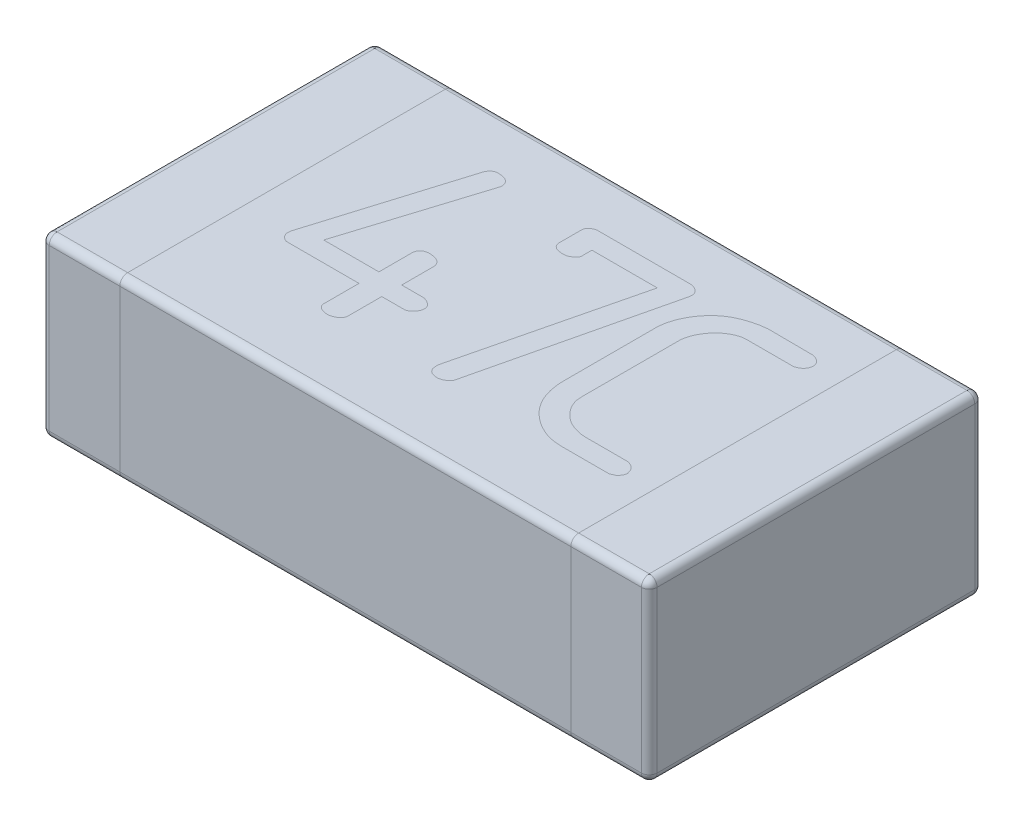
SolidWorks part; units mm, degrees
ref_plane "Front Plane" through (0, 0, 0) normal (0, 0, 1) x (1, 0, 0)
ref_plane "Top Plane" through (0, 0, 0) normal (0, 1, 0) x (1, 0, 0)
ref_plane "Right Plane" through (0, 0, 0) normal (1, 0, 0) x (0, 0, -1)
sketch "Sketch1" plane through (0, 0, 0) normal (0, 1, 0) x (1, 0, 0)
  line L1 (-0.755, -0.425) -> (0.755, -0.425)
  line L2 (-0.775, -0.405) -> (-0.775, 0.405)
  line L3 (-0.755, 0.425) -> (0.755, 0.425)
  line L4 (0.775, -0.405) -> (0.775, 0.405)
  line L5 (-0.775, -0.425) -> (0.775, 0.425) construction
  line L6 (-0.775, 0.425) -> (0.775, -0.425) construction
  arc A4 (-0.775, -0.405) -> (-0.755, -0.425) centre (-0.755, -0.405) ccw
  arc A5 (0.755, -0.425) -> (0.775, -0.405) centre (0.755, -0.405) ccw
  arc A6 (0.775, 0.405) -> (0.755, 0.425) centre (0.755, 0.405) ccw
  arc A7 (-0.755, 0.425) -> (-0.775, 0.405) centre (-0.755, 0.405) ccw
  point P0 (0, 0)
  dimension "D4" = 0.02
  dimension "D1" = 1.55
  dimension "D2" = 0.85
extrude "Boss-Extrude1" add sketch "Sketch1" along normal mid plane 0.45
sketch "Sketch3" plane through (0, 0.225, 0) normal (0, 1, 0) x (1, 0, 0)
  line L0 (-0.575, 0) -> (0.575, 0) construction
  line L1 (-0.575, -0.5133) -> (-0.575, 0.5133)
  line L2 (0.575, -0.5133) -> (0.575, 0.5133)
  line L3 (0, -0.25) -> (0, 0.25) construction
  line L6 (-0.575, -0.25) -> (0.575, -0.25) construction
  text T0 "<b>47C</b>" font "SWIsop1" height 0.53
  point P4 (0, 0)
  point P8 (-0.575, 0)
  point P11 (0.575, 0)
  point P14 (0, 0)
  point P17 (0, -0.25)
  dimension "D1" = 1.15
  dimension "D2" = 0.5
sketch "Sketch4" plane through (0, 0, 0.425) normal (0, 0, 1) x (1, 0, 0)
  line L0 (-0.575, 0.225) -> (-0.575, -0.5946)
  line L1 (0.575, 0.225) -> (0.575, -0.5946)
sketch "Sketch5" plane through (0, 0, -0.425) normal (0, 0, -1) x (-1, 0, 0)
  line L0 (-0.575, 0.225) -> (-0.575, -0.5946) construction
  line L1 (-0.575, 0.225) -> (-0.575, -0.5946)
  line L2 (0.575, 0.225) -> (0.575, -0.5946) construction
  line L3 (0.575, 0.225) -> (0.575, -0.5946)
sketch "Sketch6" plane through (0, -0.225, 0) normal (0, -1, 0) x (1, 0, 0)
  line L0 (0.575, 0.5133) -> (0.575, -0.5133) construction
  line L1 (-0.575, 0.5133) -> (-0.575, -0.5133) construction
  line L2 (0.575, 0.5133) -> (0.575, -0.5133)
  line L3 (-0.575, 0.5133) -> (-0.575, -0.5133)
split line "Split Line2"
split line "Split Line3"
split line "Split Line4"
split line "Split Line5"
fillet "Fillet2" radius 0.02 24 edges at (-0.665, -0.225, 0.425) (0, -0.225, 0.425) (0.665, -0.225, 0.425) (-0.7691, -0.225, 0.4191) (-0.775, -0.225, 0) (-0.7691, -0.225, -0.4191) (0.665, -0.225, -0.425) (0, -0.225, -0.425) (-0.665, -0.225, -0.425) (0.7691, -0.225, -0.4191) (0.775, -0.225, 0) (0.7691, -0.225, 0.4191) (-0.7691, 0.225, 0.4191) (-0.775, 0.225, 0) (-0.7691, 0.225, -0.4191) (0.665, 0.225, -0.425) (0, 0.225, -0.425) (-0.665, 0.225, -0.425) (0.7691, 0.225, -0.4191) (0.775, 0.225, 0) (0.7691, 0.225, 0.4191) (-0.665, 0.225, 0.425) (0, 0.225, 0.425) (0.665, 0.225, 0.425)
